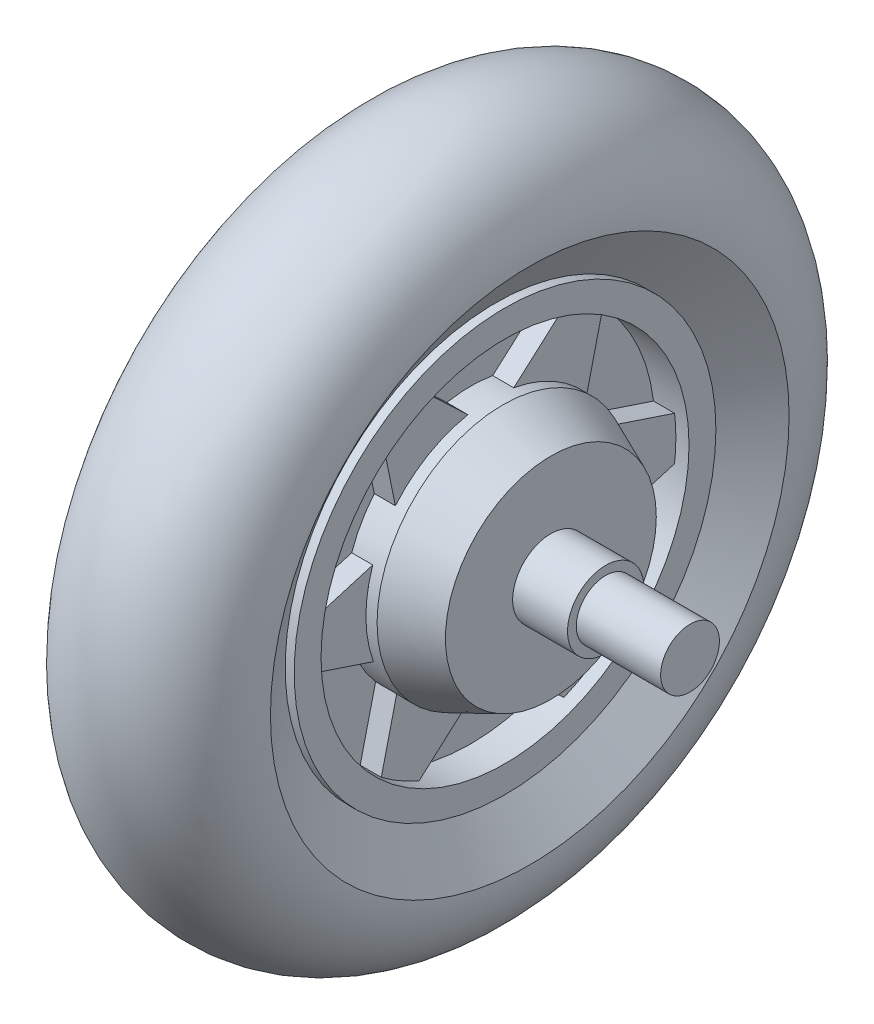
SolidWorks part; units mm, degrees
ref_plane "Front Plane" through (0, 0, 0) normal (0, 0, 1) x (1, 0, 0)
ref_plane "Top Plane" through (0, 0, 0) normal (0, 1, 0) x (1, 0, 0)
ref_plane "Right Plane" through (0, 0, 0) normal (1, 0, 0) x (0, 0, -1)
sketch "Sketch2" plane through (0, 0, 0) normal (0, 0, 1) x (1, 0, 0)
  line L0 (0, 0) -> (115.3359, 0) construction
  line L1 (0, 0) -> (0, 125.9166) construction
  line L2 (-22, 61.4891) -> (-14, 50)
  line L3 (-14, 50) -> (-8, 50)
  line L4 (8, 50) -> (14, 50)
  line L5 (14, 50) -> (22, 61.4891)
  arc A0 (22, 61.4891) -> (-22, 61.4891) centre (0, 61.4891) ccw
  arc A1 (-8, 50) -> (0, 42) centre (0, 50) ccw
  arc A2 (0, 42) -> (8, 50) centre (0, 50) ccw
  dimension "D1" = 44
  dimension "D2" = 14
  dimension "D3" = 8
  dimension "D4" = 6
  dimension "D5" = 100
revolve "Revolve1" add sketch "Sketch2" angle 360 about L0
sketch "Sketch3" plane through (0, 0, 0) normal (0, 0, 1) x (1, 0, 0)
  line L0 (-27, 0) -> (-85.7469, 0) construction
  line L1 (0, 0) -> (0, 86.1091) construction
  line L2 (-27, 9.0554) -> (-40, 9.0554)
  line L3 (-40, 9.0554) -> (-40, 6.97)
  line L4 (-8, 50) -> (-14, 50) construction
  line L5 (-40, 6.97) -> (-60, 6.97)
  line L6 (-16.1352, 50) -> (-16.1352, 43.6308)
  line L7 (27, 25) -> (27, 9.0554)
  line L8 (-8, 50) -> (-16.1352, 50)
  line L9 (-60, 6.97) -> (-60, 0)
  line L10 (-16.1352, 43.6308) -> (-8, 43.6308)
  line L11 (-8, 50) -> (-8, -50) construction
  line L12 (-8, 43.6308) -> (-8, 29.8613)
  line L13 (-8, 29.8613) -> (-15.6522, 29.8613)
  line L14 (-15.6522, 29.8613) -> (-27, 25)
  line L15 (-27, 25) -> (-27, 9.0554)
  line L16 (15.6522, 29.8613) -> (27, 25)
  line L17 (8, 29.8613) -> (15.6522, 29.8613)
  line L18 (8, 43.6308) -> (8, 29.8613)
  line L19 (16.1352, 43.6308) -> (8, 43.6308)
  line L20 (16.1352, 50) -> (16.1352, 43.6308)
  line L21 (8, 50) -> (16.1352, 50)
  line L22 (27, 0) -> (44.7833, 0) construction
  line L24 (60, 6.97) -> (60, 0)
  line L25 (40, 6.97) -> (60, 6.97)
  line L26 (27, 9.0554) -> (40, 9.0554)
  line L27 (40, 9.0554) -> (40, 6.97)
  line L28 (-60, 0) -> (60, 0)
  arc A0 (-8, 50) -> (8, 50) centre (0, 50) ccw construction
  arc A1 (-8, 50) -> (8, 50) centre (0, 50) ccw
  dimension "D1" = 54
  dimension "D2" = 20
  dimension "25" = 25
  dimension "D3" = 120
  dimension "D4" = 6.97
revolve "Revolve2" add sketch "Sketch3" angle 360 about L0
sketch "Sketch4" plane through (8, 0, 0) normal (1, 0, 0) x (0, 0, -1)
  line L0 (0, 0) -> (-50, 0) construction
  line L1 (-49.8914, 3.2936) -> (-28.2268, 9.7441)
  line L2 (-49.9151, -2.9127) -> (-28.0667, -10.196)
  circle A1 centre (0, 0) radius 50 construction
  circle A2 centre (0, 0) radius 50 construction
  circle A3 centre (0, 0) radius 29.8613 construction
  circle A4 centre (0, 0) radius 29.8613 construction
  arc A5 (-28.2268, 9.7441) -> (-28.0667, -10.196) centre (0, 0) ccw
  arc A6 (-49.8914, 3.2936) -> (-49.9151, -2.9127) centre (0, 0) ccw
extrude "Boss-Extrude2" add sketch "Sketch4" along normal blind 5
pattern_circular "CirPattern1" count 6 over 360 about axis through (0, 0, 0) along (1, 0, 0) of "Boss-Extrude2"
mirror "Mirror1" about plane through (0, 0, 0) normal (1, 0, 0) of "CirPattern1", "Boss-Extrude2"
